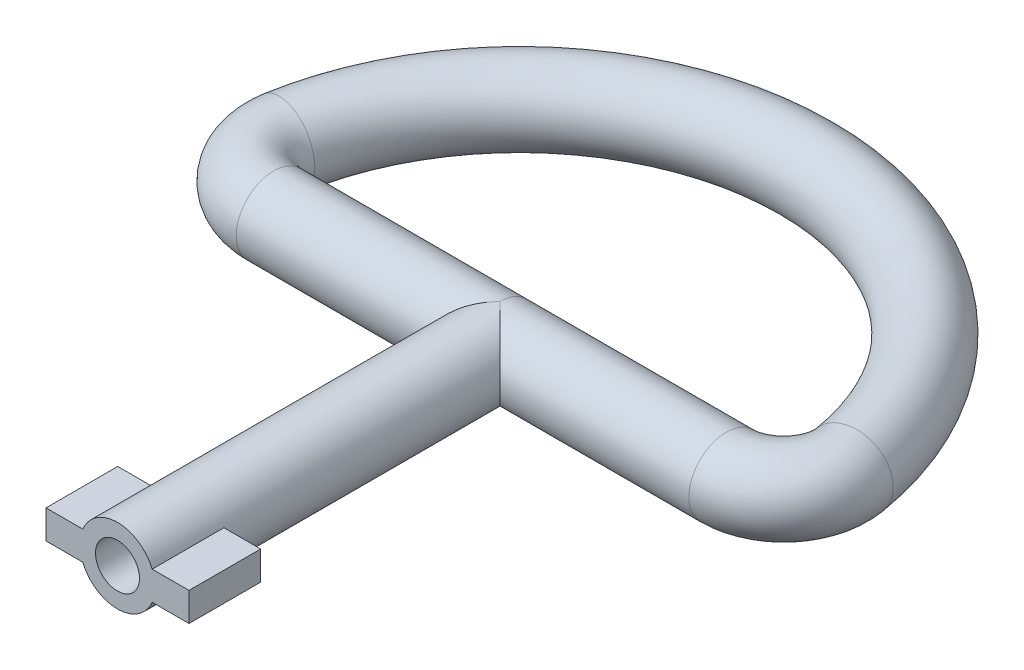
SolidWorks part; units mm, degrees
ref_plane "Alzado" through (0, 0, 0) normal (0, 0, 1) x (1, 0, 0)
ref_plane "Planta" through (0, 0, 0) normal (0, 1, 0) x (1, 0, 0)
ref_plane "Vista lateral" through (0, 0, 0) normal (1, 0, 0) x (0, 0, -1)
sketch "Croquis1" plane through (0, 0, 0) normal (0, 0, 1) x (1, 0, 0)
  line L0 (3.6271, 1.5) -> (7.475, 1.5)
  line L1 (7.475, 1.5) -> (7.475, -1.5)
  line L2 (7.475, -1.5) -> (3.6271, -1.5)
  line L3 (0, 0) -> (0, 8.465) construction
  line L4 (-7.475, -1.5) -> (-3.6271, -1.5)
  line L5 (-7.475, 1.5) -> (-7.475, -1.5)
  line L6 (-3.6271, 1.5) -> (-7.475, 1.5)
  arc A0 (-3.6271, -1.5) -> (3.6271, -1.5) centre (0, 0) ccw
  circle A1 centre (0, 0) radius 2.3
  arc A2 (3.6271, 1.5) -> (-3.6271, 1.5) centre (0, 0) ccw
  point P6 (7.475, 0)
  dimension "D2" = 7.85
  dimension "D3" = 4.6
  dimension "D1" = 3
  dimension "D4" = 14.95
extrude "Saliente-Extruir1" add sketch "Croquis1" against normal blind 7.5
sketch "Croquis4" plane through (0, 0, -7.5) normal (0, 0, -1) x (-1, 0, 0)
  circle A0 centre (0, 0) radius 3.925
  arc A1 (3.6271, 1.5) -> (-3.6271, 1.5) centre (0, 0) ccw construction
extrude "Saliente-Extruir3" add sketch "Croquis4" along normal blind 32.5
sketch "Croquis5" plane through (0, 0, 0) normal (1, 0, 0) x (0, 0, -1)
  line L0 (40, -3.925) -> (40, 3.925) construction
  line L1 (40, 3.925) -> (0, 3.925) construction
  circle A0 centre (40, 0) radius 3.925
sketch "Croquis6" plane through (0, 0, 0) normal (0, 1, 0) x (1, 0, 0)
  line L0 (0, 40) -> (23.6643, 40)
  line L1 (0, 36.075) -> (0, 43.925) construction
  line L2 (0, 40) -> (-23.6643, 40)
  arc A0 (-29.5804, 47) -> (29.5804, 47) centre (0, 42) cw
  arc A1 (23.6643, 40) -> (29.5804, 47) centre (23.6643, 46) ccw
  arc A2 (-23.6643, 40) -> (-29.5804, 47) centre (-23.6643, 46) cw
  dimension "D2" = 30
  dimension "D3" = 6
  dimension "D1" = 42
sweep "Barrer2" add profiles "Croquis5" path "Croquis6"
